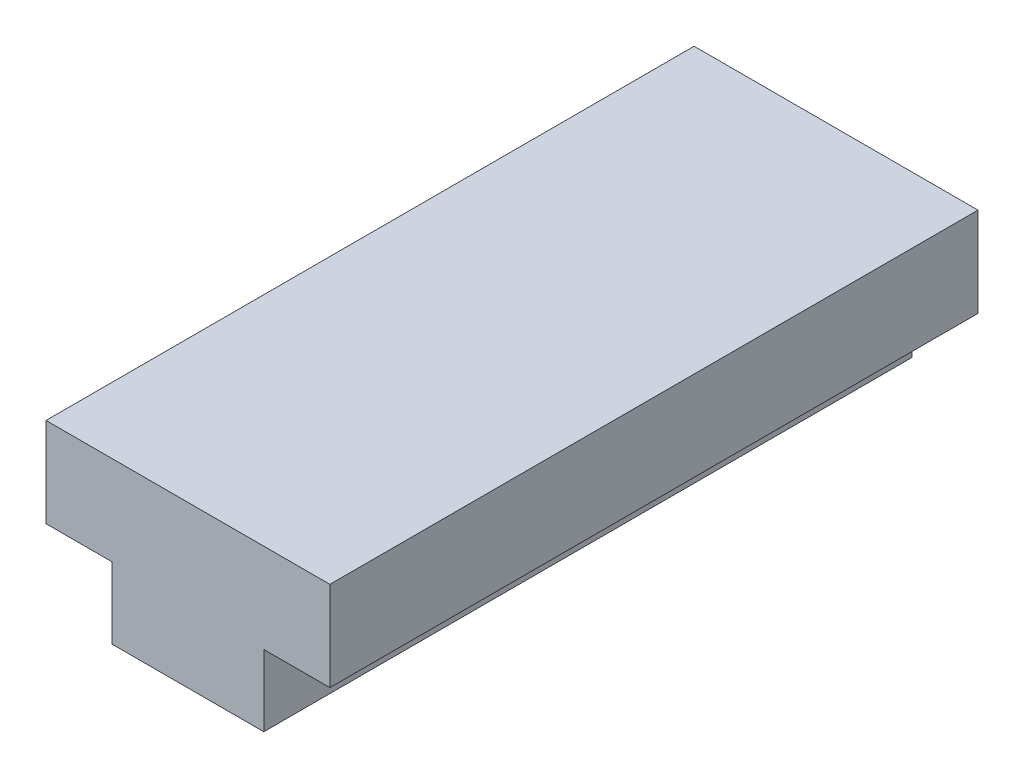
SolidWorks part; units mm, degrees
ref_plane "Спереди" through (0, 0, 0) normal (0, 0, 1) x (1, 0, 0)
ref_plane "Сверху" through (0, 0, 0) normal (0, 1, 0) x (1, 0, 0)
ref_plane "Справа" through (0, 0, 0) normal (1, 0, 0) x (0, 0, -1)
other "Configuration Table"
sketch "Sketch1" plane through (0, 0, 0) normal (0, 0, 1) x (1, 0, 0)
  line L0 (28.1483, 0) -> (5.85, 0) construction
  line L1 (0, -18.3368) -> (0, 18.3368) construction
  line L2 (-10.95, 0) -> (-5.85, 0)
  line L3 (10.95, 6.9) -> (-10.95, 6.9)
  line L4 (10.95, 6.9) -> (10.95, 0)
  line L5 (10.95, 0) -> (5.85, 0)
  line L6 (-10.95, 6.9) -> (-10.95, 0)
  line L7 (10.95, 6.9) -> (-10.95, 0) construction
  line L8 (10.95, 0) -> (-10.95, 6.9) construction
  line L9 (-5.85, 0) -> (-5.85, -5.5)
  line L10 (-5.85, -5.5) -> (5.85, -5.5)
  line L11 (5.85, 0) -> (5.85, -5.5)
  line L12 (-5.85, 0) -> (-28.1483, 0) construction
  line L13 (-5.85, 0) -> (-10.95, 0)
  point P0 (0, 3.45)
  point P4 (0, 0)
  point P8 (0, 0)
  point P16 (0, 0)
  point P17 (0, -5.5)
  point P18 (0, 0)
  point P19 (0, 0)
  point P20 (0, 0)
  dimension "D1" = 21.9
  dimension "D2" = 6.9
  dimension "D3" = 5.5
  dimension "D4" = 5.1
extrude "Boss-Extrude1" add sketch "Sketch1" against normal blind 50 contours L11 L5 L4 L3 L6 L2 L9 L10
